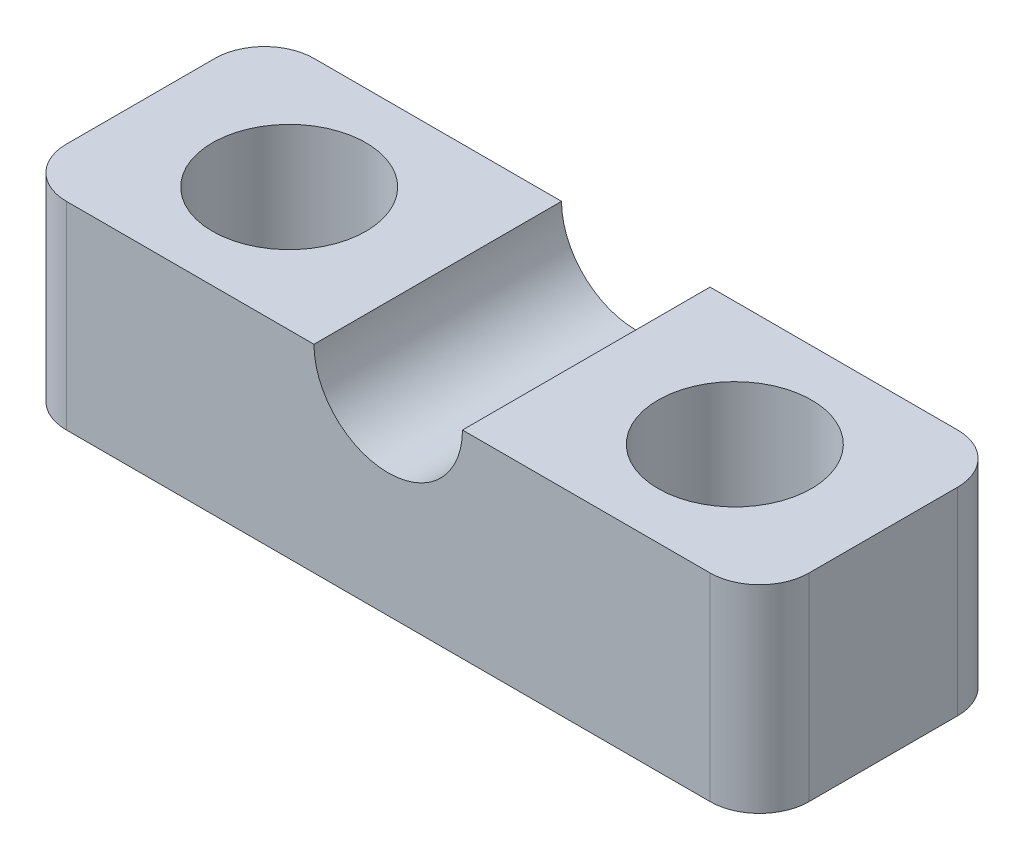
SolidWorks part; units mm, degrees
ref_plane "Front Plane" through (0, 0, 0) normal (0, 0, 1) x (1, 0, 0)
ref_plane "Top Plane" through (0, 0, 0) normal (0, 1, 0) x (1, 0, 0)
ref_plane "Right Plane" through (0, 0, 0) normal (1, 0, 0) x (0, 0, -1)
sketch "Sketch1" plane through (0, 0, 0) normal (0, 1, 0) x (1, 0, 0)
  line L1 (-4.6479, -2.1479) -> (10.3521, -2.1479)
  line L2 (-4.6479, -2.1479) -> (-4.6479, 2.8521)
  line L3 (-4.6479, 2.8521) -> (10.3521, 2.8521)
  line L4 (10.3521, -2.1479) -> (10.3521, 2.8521)
  dimension "D1" = 5
  dimension "D2" = 15
extrude "Boss-Extrude1" add sketch "Sketch1" along normal blind 4
sketch "Sketch2" plane through (0, 0, -2.8521) normal (0, 0, -1) x (-1, 0, 0)
  line L0 (-10.3521, 4) -> (4.6479, 4) construction
  circle A0 centre (-2.8521, 4) radius 1.5
  dimension "D1" = 3
extrude "Cut-Extrude1" cut sketch "Sketch2" against normal through all and the other way through all
sketch "Sketch3" plane through (0, 4, 0) normal (0, 1, 0) x (1, 0, 0)
  line L0 (1.3521, 2.8521) -> (-4.6479, 2.8521) construction
  line L1 (-4.6479, 2.8521) -> (-4.6479, -2.1479) construction
  line L2 (10.3521, 2.8521) -> (4.3521, 2.8521) construction
  circle A0 centre (-1.6479, 0.3521) radius 1.55
  circle A1 centre (7.3521, 0.3521) radius 1.55
  point P6 (-1.6479, 2.8521)
  point P7 (0, 0)
  point P10 (-4.6479, 0.3521)
  point P11 (0, 0)
  point P12 (0, 0)
  point P15 (7.3521, 2.8521)
  dimension "D1" = 3.1
  dimension "D2" = 3.1
extrude "Cut-Extrude2" cut sketch "Sketch3" against normal through all
fillet "Fillet1" radius 1 4 edges at (-4.6479, 2, 2.1479) (10.3521, 2, 2.1479) (-4.6479, 2, -2.8521) (10.3521, 2, -2.8521)
